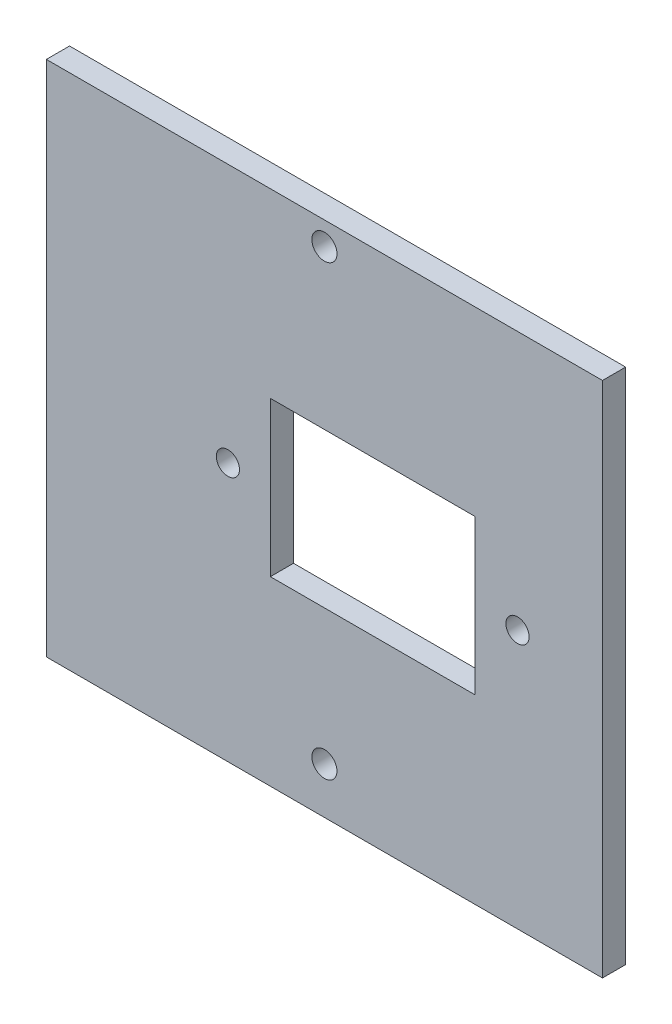
SolidWorks part; units mm, degrees
ref_plane "Alzado" through (0, 0, 0) normal (0, 0, 1) x (1, 0, 0)
ref_plane "Planta" through (0, 0, 0) normal (0, 1, 0) x (1, 0, 0)
ref_plane "Vista lateral" through (0, 0, 0) normal (1, 0, 0) x (0, 0, -1)
sketch "Croquis1" plane through (0, 0, 0) normal (0, 0, 1) x (1, 0, 0)
  line B0 (47.0497, -53.14) -> (47.0497, 13.86)
  line B1 (47.0497, 13.86) -> (119.0497, 13.86)
  line B2 (47.0497, -53.14) -> (119.0497, -53.14)
  line B3 (119.0497, -53.14) -> (119.0497, 13.86)
sketch_block_instance "Bloque-Croquis2-1"
sketch_block "Bloque-Croquis2" parameters "D1"=50, "D2"=59.9093
extrude "Saliente-Extruir1" add sketch "Croquis1" along normal blind 3
sketch "Croquis4" plane through (0, 0, 0) normal (0, 0, -1) x (-1, 0, 0)
  line L0 (-102.5497, -29.64) -> (-76.0497, -9.64) construction
  line L2 (-76.0497, -9.64) -> (-76.0497, -29.64)
  line L3 (-76.0497, -29.64) -> (-102.5497, -29.64)
  line L4 (-102.5497, -9.64) -> (-102.5497, -29.64)
  line L5 (-119.0497, -53.14) -> (-119.0497, 13.86) construction
  line L6 (-47.0497, -53.14) -> (-119.0497, -53.14) construction
  line L11 (-102.5497, -9.64) -> (-76.0497, -9.64)
  line L12 (-119.0497, 13.86) -> (-47.0497, 13.86) construction
  circle A0 centre (-83.0497, -47.14) radius 1.625 construction
  circle A2 centre (-83.0497, -47.14) radius 1.625
  circle A3 centre (-83.0497, 10.86) radius 1.625
  circle A4 centre (-108.0497, -19.64) radius 1.5
  circle A5 centre (-70.5497, -19.64) radius 1.5
  point P15 (-89.2997, -19.64)
  point P20 (0, 0)
  dimension "D6" = 5.5
  dimension "D7" = 3
  dimension "D8" = 3.25
  dimension "D9" = 3
  dimension "D1" = 16.5
  dimension "D2" = 23.5
  dimension "D3" = 26.5
  dimension "D4" = 20
  dimension "D5" = 5.5
extrude "Cortar-Extruir2" cut sketch "Croquis4" against normal blind 3
